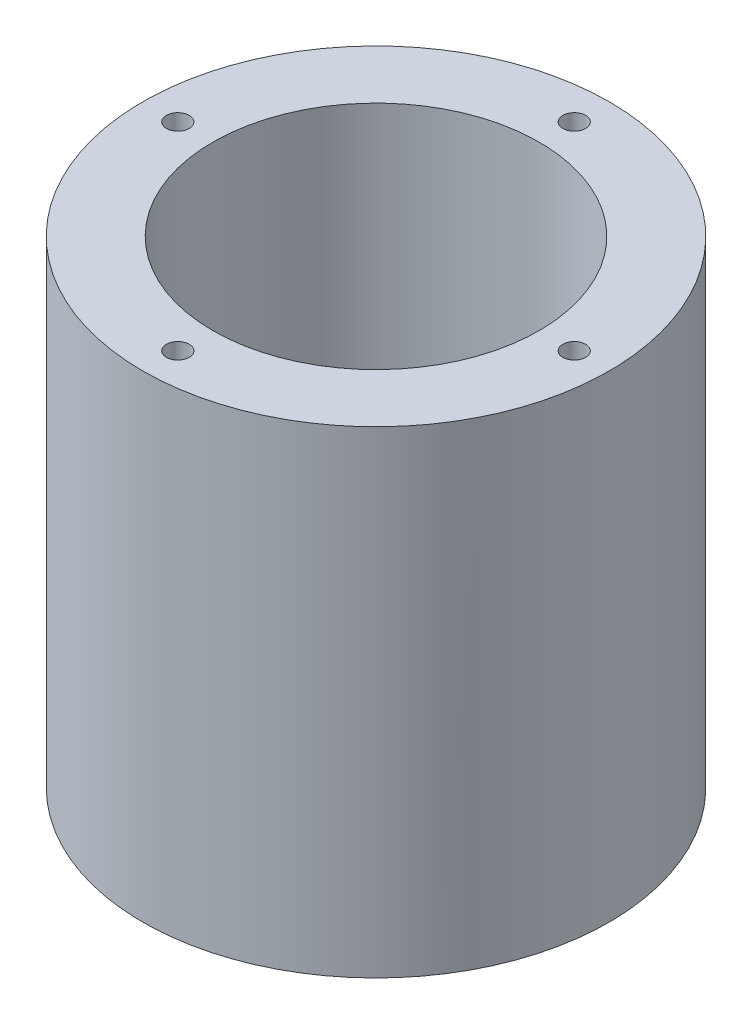
SolidWorks part; units mm, degrees
ref_plane "Front Plane" through (0, 0, 0) normal (0, 0, 1) x (1, 0, 0)
ref_plane "Top Plane" through (0, 0, 0) normal (0, 1, 0) x (1, 0, 0)
ref_plane "Right Plane" through (0, 0, 0) normal (1, 0, 0) x (0, 0, -1)
sketch "Sketch1" plane through (0, 0, 0) normal (0, 1, 0) x (1, 0, 0)
  circle A0 centre (0, 0) radius 31.75
  circle A1 centre (0, 0) radius 22.225
  dimension "D1" = 63.5
  dimension "D2" = 44.45
extrude "Boss-Extrude1" add sketch "Sketch1" along normal blind 55
sketch "Sketch2" plane through (0, 0, 0) normal (0, -1, 0) x (1, 0, 0)
  circle A0 centre (0, 0) radius 31.75
extrude "Boss-Extrude2" add sketch "Sketch2" along normal blind 10
sketch "Sketch3" plane through (0, 55, 0) normal (0, 1, 0) x (1, 0, 0)
  circle A0 centre (0, 26.9875) radius 1.55
  circle A1 centre (26.9875, 0) radius 1.55
  circle A2 centre (0, -26.9875) radius 1.55
  circle A3 centre (-26.9875, 0) radius 1.55
  point P11 (0, 0)
  dimension "D1" = 4
extrude "Cut-Extrude1" cut sketch "Sketch3" against normal blind 5
sketch "Sketch7" plane through (0, -10, 0) normal (0, -1, 0) x (-1, 0, 0)
  circle A0 centre (19.05, 0) radius 3
  circle A1 centre (-19.05, 0) radius 3
  dimension "D1" = 2
extrude "Cut-Extrude2" cut sketch "Sketch7" against normal blind 10
